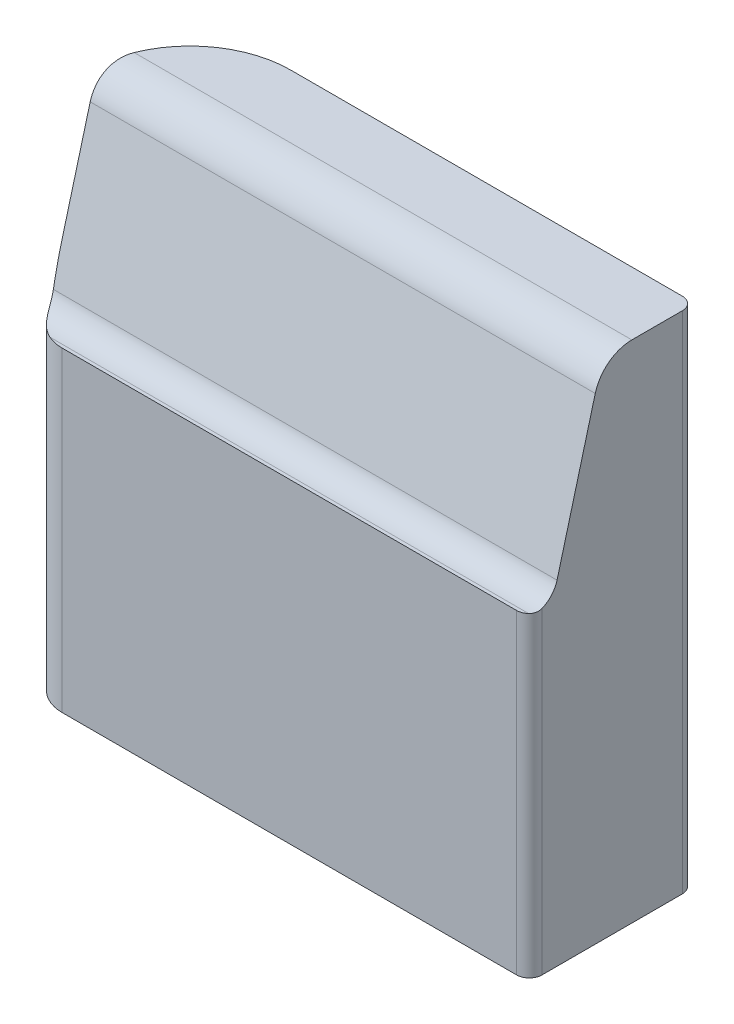
SolidWorks part; units mm, degrees
material "K110"
ref_plane "Front Plane" through (0, 0, 0) normal (0, 0, 1) x (1, 0, 0)
ref_plane "Top Plane" through (0, 0, 0) normal (0, 1, 0) x (1, 0, 0)
ref_plane "Right Plane" through (0, 0, 0) normal (1, 0, 0) x (0, 0, -1)
sketch "Sketch1" plane through (0, 0, 0) normal (1, 0, 0) x (0, 0, -1)
  line L0 (-5, 0) -> (0, 0)
  line L1 (0, 0) -> (0, -40)
  line L2 (0, -40) -> (-13.12, -40)
  line L3 (-13.12, -40) -> (-13.12, -15)
  line L4 (-13.12, -15) -> (-11.3212, -15)
  line L5 (-11.3212, -15) -> (-7.8978, -2.2235)
  arc A0 (-7.8978, -2.2235) -> (-5, 0) centre (-5, -3) cw
  dimension "D2" = 3
  dimension "D1" = 5
  dimension "D3" = 40
  dimension "D4" = 25
  dimension "D5" = 75
  dimension "D6" = 13.12
extrude "Boss-Extrude1" add sketch "Sketch1" along normal mid plane 40
fillet "Fillet1" radius 1 2 edges at (20, -20, 0) (20, -27.5, 13.12)
fillet "Fillet2" radius 2 1 edges at (0, -15, 11.3212)
fillet "Fillet3" radius 8 1 edges at (-20, -20, 0)
fillet "Fillet4" radius 3 1 edges at (-20, -27.5, 13.12)
hole_wizard "M6 Tapped Hole1" positions "Sketch4" profile "Sketch3" tap size "M6" standard "ISO"
sketch "Sketch4" plane through (0, -40, 0) normal (0, -1, 0) x (-1, 0, 0)
  line L0 (-20, -6.56) -> (19.8693, -6.56) construction
  line L1 (-20, -12.12) -> (-20, -1) construction
  arc A0 (20, -8) -> (12, 0) centre (12, -8) ccw construction
  point P0 (-13, -6.56)
  point P2 (9.8693, -6.56)
  dimension "D1" = 7
  dimension "D2" = 10
sketch "Sketch3" plane through (13, -40, 6.56) normal (1, 0, 0) x (0, 0, -1)
  line L0 (0, 0) -> (0, 16.5022)
  line L1 (0, 16.5022) -> (2.5, 15)
  line L2 (2.5, 15) -> (2.5, 0.525)
  line L3 (2.5, 0.525) -> (3.025, 0)
  line L5 (3.025, 0) -> (0, 0)
  line L6 (-2.5, 0.525) -> (-3.025, 0) construction
  line L10 (0, 16.5022) -> (-2.5, 15) construction
  line L11 (0, -6.35) -> (0, 107.95) construction
  dimension "Tap Drill Dia." = 5
  dimension "Tap Drill Depth" = 15
  dimension "Near C'Sink Dia." = 6.05
  dimension "Near C'Sink Angle" = 90
  dimension "Drill Angle" = 118
cosmetic thread "Hole Thread1"
cosmetic thread "Hole Thread2"
